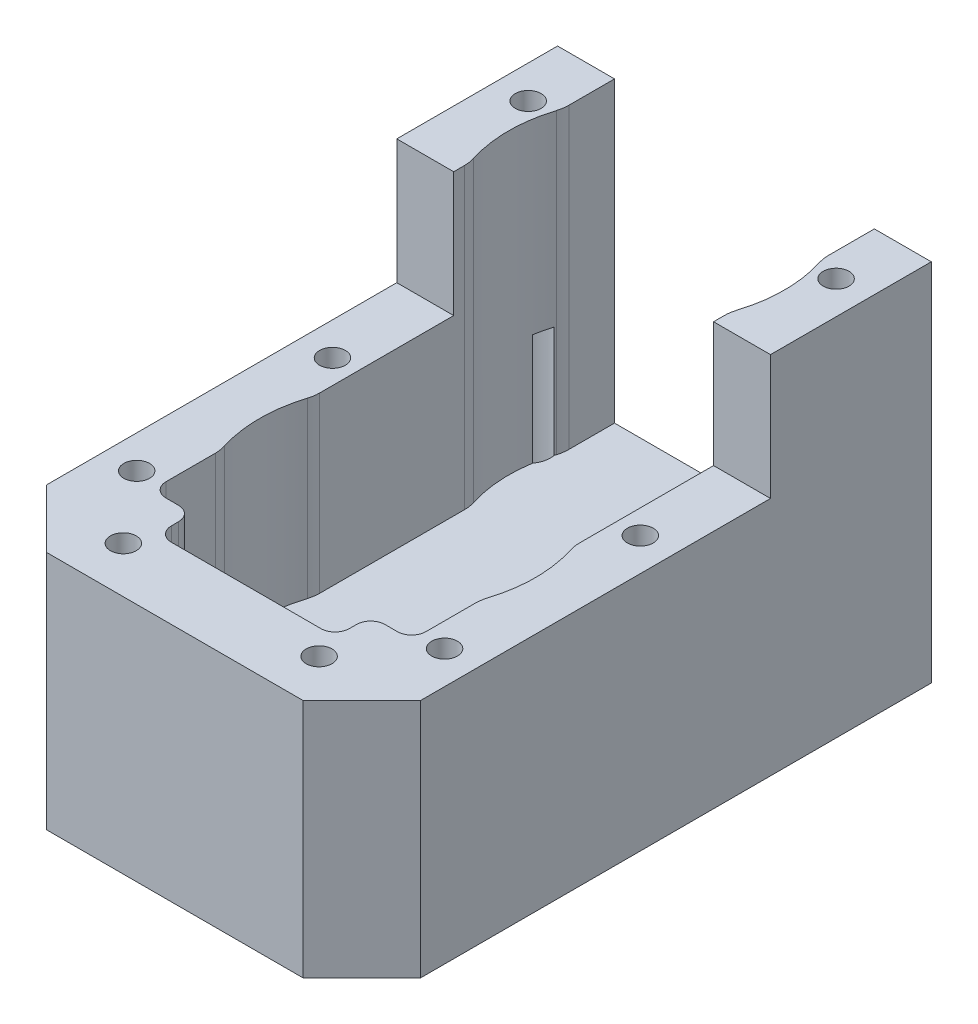
SolidWorks part; units mm, degrees
material "6061-T6 (SS)"
ref_plane "Front Plane" through (0, 0, 0) normal (0, 0, 1) x (1, 0, 0)
ref_plane "Top Plane" through (0, 0, 0) normal (0, 1, 0) x (1, 0, 0)
ref_plane "Right Plane" through (0, 0, 0) normal (1, 0, 0) x (0, 0, -1)
sketch "Sketch1" plane through (0, 0, 0) normal (0, 1, 0) x (1, 0, 0)
  line L1 (-40, 30) -> (0, 30)
  line L2 (-40, 30) -> (-40, -30)
  line L3 (-40, -30) -> (0, -30)
  line L4 (0, 30) -> (0, -30)
  point P6 (0, 0)
  dimension "D1" = 60
  dimension "D2" = 40
extrude "Boss-Extrude1" add sketch "Sketch1" along normal blind 41
sketch "Sketch2" plane through (0, 41, 0) normal (0, 1, 0) x (1, 0, 0)
  line L0 (-37.3, 26) -> (-2.7, 26)
  line L1 (-20, -30) -> (-20, -25.8) construction
  line L2 (-20, 26) -> (-20, 30) construction
  line L3 (0, 30) -> (-40, 30) construction
  line L4 (-37.3, 4) -> (-2.7, 4)
  line L5 (-37.3, -18) -> (-2.7, -18)
  line L6 (-31, -25.8) -> (-9, -25.8)
  line L7 (-40, -30) -> (0, -30) construction
  point P17 (-37.3, 26)
  point P18 (-37.3, 4)
  point P19 (-37.3, -18)
  point P20 (-31, -25.8)
  point P21 (-9, -25.8)
  point P22 (-2.7, -18)
  point P23 (-2.7, 4)
  point P24 (-2.7, 26)
  dimension "D1" = 34.6
  dimension "D2" = 4
  dimension "D4" = 7.8
  dimension "D5" = 22
  dimension "D6" = 22
  dimension "D3" = 3
hole_wizard "M2.5 Clearance Hole1" positions "Sketch2" profile "Sketch3" hole size "M2.5" standard "DIN" end condition through all
sketch "Sketch3" plane through (-37.3, 41, -26) normal (1, 0, 0) x (0, 0, 1)
  line L0 (0, 0) -> (0, 41)
  line L1 (0, 41) -> (1.45, 41)
  line L2 (1.45, 41) -> (1.45, 0)
  line L5 (1.45, 0) -> (0, 0)
  line L11 (0, -6.35) -> (0, 107.95) construction
  dimension "Thru Hole Dia." = 2.9
  dimension "Thru Hole Depth" = 41
sketch "Sketch4" plane through (0, 41, 0) normal (0, 1, 0) x (1, 0, 0)
  line L1 (0, 30) -> (-40, 30) construction
  line L3 (-34.6, 30) -> (-34.6, -19)
  line L4 (-34.6, -19) -> (-30, -19)
  line L5 (-30, -19) -> (-30, -23)
  line L6 (-30, -23) -> (-10, -23)
  line L7 (-10, -23) -> (-10, -19)
  line L8 (-10, -19) -> (-5.4, -19)
  line L9 (-5.4, -19) -> (-5.4, 30)
  line L12 (-5.4, 30) -> (-34.6, 30)
  line L13 (-20, -23) -> (-20, -30) construction
  line L14 (-40, -30) -> (0, -30) construction
  dimension "D1" = 29.2
  dimension "D2" = 20
  dimension "D3" = 4
  dimension "D5" = 53
extrude "Cut-Extrude1" cut sketch "Sketch4" against normal blind 33.5
fillet "Fillet1" radius 1.6 6 edges at (-30, 24.25, 19) (-34.6, 24.25, 19) (-5.4, 24.25, 19) (-10, 24.25, 19) (-10, 24.25, 23) (-30, 24.25, 23)
sketch "Sketch7" plane through (0, 7.5, 0) normal (0, 1, 0) x (1, 0, 0)
  line L0 (-20, 30) -> (-20, -32.9837) construction
  line L1 (-5.4, 30) -> (-34.6, 30) construction
  circle A0 centre (-31, -25.8) radius 1.45 construction
  point P0 (-20, 22)
  point P11 (-20, -6)
  dimension "D1" = 47.8
  dimension "D2" = 28
hole_wizard "Ø16.0 (16) Diameter Hole2" positions "Sketch7" profile "Sketch6" hole size "Ø16.0" standard "DIN"
sketch "Sketch6" plane through (-20, 7.5, 6) normal (1, 0, 0) x (0, 0, 1)
  line L0 (0, 0) -> (0, 7.5)
  line L1 (0, 7.5) -> (8, 7.5)
  line L2 (8, 7.5) -> (8, 0)
  line L5 (8, 0) -> (0, 0)
  line L11 (0, -6.35) -> (0, 107.95) construction
  dimension "Thru Hole Dia." = 16
  dimension "Thru Hole Depth" = 7.5
sketch "Sketch9" plane through (0, 7.5, 0) normal (0, 1, 0) x (1, 0, 0)
  circle A1 centre (-20, -6) radius 15.5
  dimension "D2" = 31
extrude "Cut-Extrude2" cut sketch "Sketch9" along normal up to surface (33.5 mm away) up to face at (-20, 41, 10.0813)
fillet "Fillet2" radius 4 4 edges at (-34.6, 24.25, 11.2048) (-34.6, 24.25, 0.7952) (-5.4, 24.25, 0.7952) (-5.4, 24.25, 11.2048)
sketch "Sketch11" plane through (0, 41, 0) normal (0, 1, 0) x (1, 0, 0)
  line L0 (-34.6, 30) -> (-34.6, -0.1442) construction
  line L1 (-44.9411, -38.411) -> (5.7125, -38.411)
  line L2 (-44.9411, -38.411) -> (-44.9411, 14.9279)
  line L3 (-44.9411, 14.9279) -> (5.7125, 14.9279)
  line L4 (5.7125, -38.411) -> (5.7125, 14.9279)
  point P6 (-34.6, 14.9279)
extrude "Cut-Extrude3" cut sketch "Sketch11" against normal blind 14 and the other way through all
sketch "Sketch12" plane through (0, 7.5, 0) normal (0, 1, 0) x (1, 0, 0)
  line L0 (-20, -6) -> (-20, 22) construction
  circle A0 centre (-20, 22) radius 15.5
  dimension "D2" = 31
  dimension "D1" = 28
extrude "Cut-Extrude4" cut sketch "Sketch12" along normal through all
fillet "Fillet3" radius 4 4 edges at (-5.4, 24.25, -16.7952) (-5.4, 24.25, -27.2048) (-34.6, 24.25, -27.2048) (-34.6, 24.25, -16.7952)
sketch "Sketch15" plane through (0, 0, -30) normal (0, 0, -1) x (-1, 0, 0)
  line L8 (40, 41) -> (34.6, 41)
  line L9 (34.6, 41) -> (34.6, 7.5)
  line L10 (34.6, 7.5) -> (5.4, 7.5)
  line L11 (5.4, 7.5) -> (5.4, 41)
  line L12 (5.4, 41) -> (0, 41)
  line L13 (0, 41) -> (0, 0)
  line L14 (0, 0) -> (40, 0)
  line L15 (40, 0) -> (40, 41)
  line L16 (40, 41) -> (34.6, 41)
  line L17 (34.6, 41) -> (34.6, 7.5)
  line L18 (34.6, 7.5) -> (5.4, 7.5)
  line L19 (5.4, 7.5) -> (5.4, 41)
  line L20 (5.4, 41) -> (0, 41)
  line L21 (0, 41) -> (0, 0)
  line L22 (0, 0) -> (40, 0)
  line L23 (40, 0) -> (40, 41)
  dimension "D1" = 0
extrude "Boss-Extrude3" add sketch "Sketch15" along normal blind 3
chamfer "Chamfer1" distance 6 angle 45 2 edges at (-40, 13.5, 30) (0, 13.5, 30)
sketch "Sketch18" plane through (0, 0, 0) normal (0, -1, 0) x (1, 0, 0)
  line L0 (0, 24) -> (0, -33) construction
  line L1 (0, 24) -> (-6, 30) construction
  line L2 (-34, 30) -> (-6, 30) construction
  line L3 (-34, 30) -> (-40, 24) construction
  line L4 (-40, -33) -> (-40, 24) construction
  line L5 (0, 24) -> (0, -33)
  line L6 (0, 24) -> (-6, 30)
  line L7 (-34, 30) -> (-6, 30)
  line L8 (-34, 30) -> (-40, 24)
  line L9 (-40, -33) -> (-40, 24)
  line L10 (-41, -33) -> (-41, 24.4142)
  line L11 (-34.4142, 31) -> (-41, 24.4142)
  line L12 (-34.4142, 31) -> (-5.5858, 31)
  line L13 (1, 24.4142) -> (-5.5858, 31)
  line L14 (1, 24.4142) -> (1, -33)
  line L15 (-41, -33) -> (-40, -33)
  line L16 (1, -33) -> (0, -33)
  dimension "D1" = 1
extrude "Boss-Extrude4" add sketch "Sketch18" against normal up to surface (41 mm away) up to face at (-37.3, 41, -24.55)
sketch "Sketch19" plane through (0, 0, 0) normal (-1, 0, 0) x (0, 0, 1)
  line L1 (-14.9279, 27) -> (33.7392, 27)
  line L2 (-14.9279, 27) -> (-14.9279, 45.2047)
  line L3 (-14.9279, 45.2047) -> (33.7392, 45.2047)
  line L4 (33.7392, 27) -> (33.7392, 45.2047)
extrude "Cut-Extrude5" cut sketch "Sketch19" against normal through all and the other way through all
sketch "Sketch16" plane through (0, 0, 0) normal (0, -1, 0) x (-1, 0, 0)
  point P0 (2.7, 4)
  point P3 (37.3, 4)
  point P6 (37.3, -18)
  point P9 (31, -25.8)
  point P12 (9, -25.8)
  point P15 (2.7, -18)
  point P19 (2.7, 26)
  point P22 (37.3, 26)
hole_wizard "CBORE for M2.5 Hex Socket Head Cap Screw1" positions "Sketch16" profile "Sketch17" counterbore size "M2.5" standard "DIN" end condition through all
sketch "Sketch17" plane through (-2.7, 0, -4) normal (1, 0, 0) x (0, 0, -1)
  line L0 (0, 0) -> (0, 41)
  line L1 (0, 41) -> (1.45, 41)
  line L3 (1.45, 41) -> (1.45, 20)
  line L4 (1.45, 20) -> (2.5, 20)
  line L5 (2.5, 20) -> (2.5, 0)
  line L7 (2.5, 0) -> (0, 0)
  line L11 (0, -6.35) -> (0, 107.95) construction
  dimension "Thru Hole Dia." = 2.9
  dimension "Thru Hole Depth" = 41
  dimension "C'Bore Dia." = 5
  dimension "C'Bore Depth" = 20
sketch "Sketch22" plane through (0, 0, -33) normal (0, 0, -1) x (-1, 0, 0)
  line L4 (8, 3.75) -> (32, 3.75) construction
  line L5 (2.2, 41) -> (2.2, 35) construction
  line L6 (5.4, 41) -> (-1, 41) construction
  line L7 (20, 7.5) -> (20, 0) construction
  line L8 (28.4, 7.5) -> (11.6, 7.5) construction
  line L9 (-1, 0) -> (41, 0) construction
  point P9 (8, 3.75)
  point P10 (32, 3.75)
  point P13 (20, 3.75)
  point P18 (8, 3.75)
  point P21 (32, 3.75)
  point P26 (2.2, 35)
  point P33 (2.2, 35)
  point P39 (37.8, 35)
  dimension "D1" = 24
  dimension "D2" = 6
hole_wizard "Tap Drill for M3 Helicoil1" positions "Sketch22" profile "Sketch24" hole size "M3x0.5" standard "DIN"
sketch "Sketch24" plane through (-37.8, 35, -33) normal (1, 0, 0) x (0, 1, 0)
  line L0 (0, 0) -> (0, 4.9614)
  line L1 (0, 4.9614) -> (1.6, 4)
  line L2 (1.6, 4) -> (1.6, 0)
  line L5 (1.6, 0) -> (0, 0)
  line L10 (0, 4.9614) -> (-1.6, 4) construction
  line L11 (0, -6.35) -> (0, 107.95) construction
  dimension "Hole Dia." = 3.2
  dimension "Hole Depth" = 4
  dimension "Drill Angle" = 118
sketch "Sketch25" plane through (-41, 0, 0) normal (-1, 0, 0) x (0, 0, 1)
  line L0 (-6.5, 0) -> (-1.5, 0) construction
  line L1 (-6.5, 0) -> (-1.5, 0) construction
  line L2 (-4, 0) -> (-4, 27) construction
  line L4 (-14.9279, 27) -> (24.4142, 27) construction
  line L5 (-28.5, 0) -> (-23.5, 0) construction
  line L6 (15.5, 0) -> (20.5, 0) construction
  line L7 (-28.5, 0) -> (-23.5, 0) construction
  line L8 (15.5, 0) -> (20.5, 0) construction
  line L9 (-26, 0) -> (-26, 41) construction
  line L10 (-14.9279, 41) -> (-33, 41) construction
  line L12 (18, 0) -> (18, 27) construction
  line L14 (18, 13.5) -> (-26, 13.5) construction
  line L16 (18, 0) -> (18, 13.5)
  line L17 (18, 13.5) -> (-4, 13.5)
  line L18 (18, 6.75) -> (-4, 6.75) construction
  line L20 (7, 13.5) -> (7, 6.75) construction
  point P38 (7, 13.5)
  point P40 (7, 6.75)
  point P48 (7, 20.25)
  point P50 (-15, 6.75)
  point P51 (-15, 13.5)
  point P52 (-15, 20.25)
  point P53 (7, 13.5)
  point P55 (7, 6.75)
hole_wizard "Tap Drill for M3 Helicoil2" positions "Sketch25" profile "Sketch26" hole size "M3x0.5" standard "DIN"
sketch "Sketch26" plane through (-41, 6.75, 7) normal (0, 1, 0) x (0, 0, 1)
  line L0 (0, 0) -> (0, 5.4464)
  line L1 (0, 5.4464) -> (1.575, 4.5)
  line L2 (1.575, 4.5) -> (1.575, 0)
  line L5 (1.575, 0) -> (0, 0)
  line L10 (0, 5.4464) -> (-1.575, 4.5) construction
  line L11 (0, -6.35) -> (0, 107.95) construction
  dimension "Hole Dia." = 3.15
  dimension "Hole Depth" = 4.5
  dimension "Drill Angle" = 118
ref_plane "Plane1" through (0, 0, -4) normal (0, 0, 1) x (0, 1, 0)
